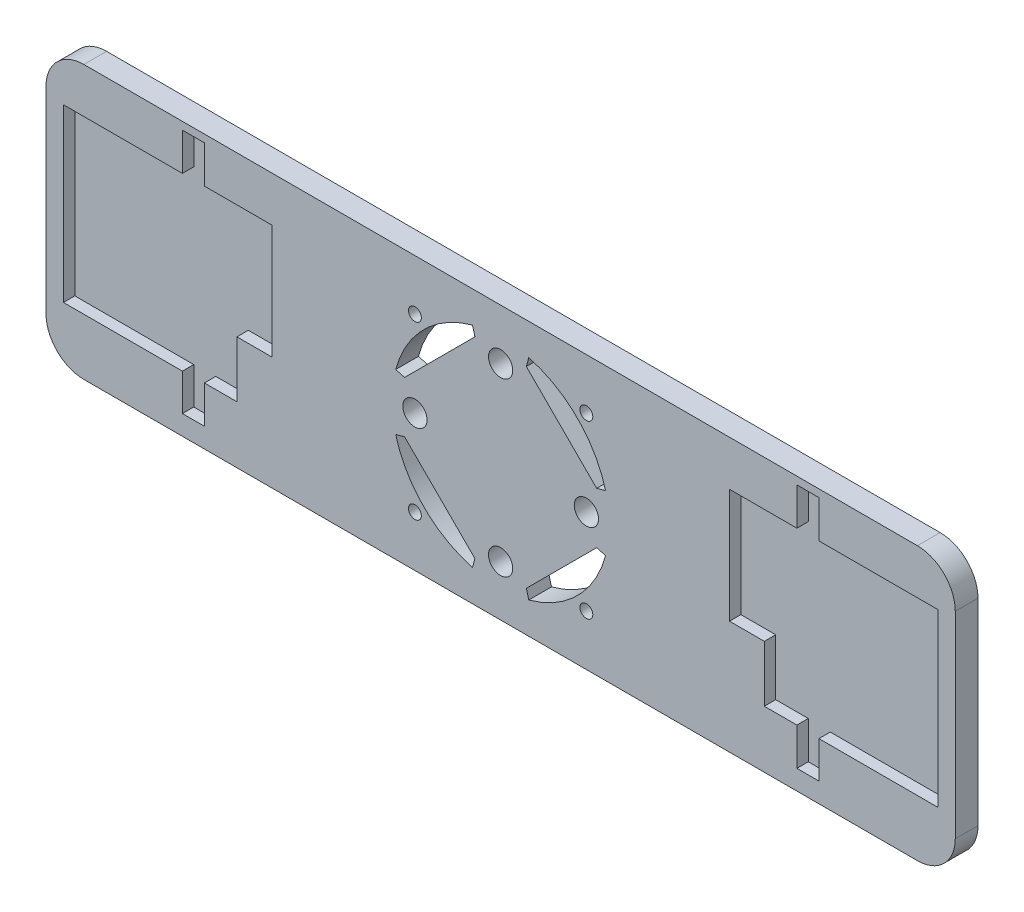
SolidWorks part; units mm, degrees
ref_plane "前视基准面" through (0, 0, 0) normal (0, 0, 1) x (1, 0, 0)
ref_plane "上视基准面" through (0, 0, 0) normal (0, 1, 0) x (1, 0, 0)
ref_plane "右视基准面" through (0, 0, 0) normal (1, 0, 0) x (0, 0, -1)
sketch "草图1" plane through (0, 0, 0) normal (0, 0, 1) x (1, 0, 0)
  line L0 (60, 32.3394) -> (60, 27.7137) construction
  line L1 (0, 0) -> (120, 0)
  line L2 (0, 0) -> (0, 36)
  line L3 (0, 36) -> (120, 36)
  line L4 (120, 0) -> (120, 36)
  line L5 (45.6606, 18) -> (50.2863, 18) construction
  line L6 (54.3431, 23.6569) -> (51.9667, 26.0333) construction
  line L9 (69.2761, 27.2761) -> (87.5831, 45.5831) construction
  line L11 (65.6569, 12.3431) -> (68.0333, 9.9667) construction
  line L12 (50.7239, 8.7239) -> (42.6818, 0.6818) construction
  line L13 (56.6047, 30.6714) -> (56.2887, 31.8508)
  line L14 (63.3953, 30.6714) -> (63.7113, 31.8508)
  line L15 (72.6714, 21.3953) -> (73.8508, 21.7113)
  line L16 (63.3953, 5.3286) -> (63.7113, 4.1492)
  line L17 (72.6714, 14.6047) -> (73.8508, 14.2887)
  line L18 (47.3286, 21.3953) -> (46.1492, 21.7113)
  line L19 (47.3286, 14.6047) -> (46.1492, 14.2887)
  line L20 (56.6047, 5.3286) -> (56.2887, 4.1492)
  line L21 (60, 8.2863) -> (60, 0) construction
  line L22 (69.7137, 18) -> (74.3394, 18) construction
  line L23 (56.6047, 30.6714) -> (47.3286, 21.3953)
  line L24 (47.3286, 14.6047) -> (56.6047, 5.3286)
  line L25 (63.3953, 5.3286) -> (72.6714, 14.6047)
  line L26 (63.3953, 30.6714) -> (72.6714, 21.3953)
  line L27 (50.7239, 27.2761) -> (32.4301, 45.5699) construction
  line L28 (69.2761, 8.7239) -> (76.9756, 1.0244) construction
  circle A8 centre (48.6863, 29.3137) radius 0.85
  circle A9 centre (48.6863, 6.6863) radius 0.85
  circle A10 centre (71.3137, 6.6863) radius 0.85
  circle A11 centre (71.3137, 29.3137) radius 0.85
  circle A16 centre (60, 29.3137) radius 1.6
  circle A17 centre (48.6863, 18) radius 1.6
  circle A18 centre (60, 6.6863) radius 1.6
  circle A19 centre (71.3137, 18) radius 1.6
  arc A23 (46.1492, 14.2887) -> (56.2887, 4.1492) centre (60, 18) ccw
  arc A25 (73.8508, 21.7113) -> (63.7113, 31.8508) centre (60, 18) ccw
  arc A27 (56.2887, 31.8508) -> (46.1492, 21.7113) centre (60, 18) ccw
  arc A28 (63.7113, 4.1492) -> (73.8508, 14.2887) centre (60, 18) ccw
  dimension "D3" = 16
  dimension "D4" = 16
  dimension "D5" = 1.7
  dimension "D6" = 1.7
  dimension "D7" = 8
  dimension "D10" = 15
  dimension "D11" = 15
  dimension "D9" = 3.2
  dimension "D1" = 120
  dimension "D2" = 36
  dimension "D8" = 8
  dimension "D16" = 45
  dimension "D17" = 45
  dimension "D18" = 45
  dimension "D19" = 45
extrude "凸台-拉伸1" add sketch "草图1" along normal blind 3
sketch "草图2" plane through (0, 0, 3) normal (0, 0, 1) x (1, 0, 0)
  line L1 (0, 36) -> (0, 0) construction
  line L2 (120, 0) -> (120, 36) construction
  line L3 (60, 36) -> (60, 0) construction
  line L4 (120, 36) -> (0, 36) construction
  line L5 (0, 0) -> (120, 0) construction
  line L18 (93, 18) -> (120, 18) construction
  line L88 (2.3, 30.05) -> (18, 30.05)
  line L93 (18, 30.05) -> (18, 35)
  line L94 (18, 35) -> (20.9, 35)
  line L95 (20.9, 35) -> (20.9, 30.05)
  line L96 (20.9, 30.05) -> (29.8, 30.05)
  line L98 (29.8, 30.05) -> (29.8, 14.97)
  line L99 (29.8, 14.97) -> (25.2, 14.97)
  line L100 (25.2, 14.97) -> (25.2, 7.55)
  line L101 (25.2, 7.55) -> (20.9, 7.55)
  line L102 (20.9, 7.55) -> (20.9, 2.6)
  line L103 (20.9, 2.6) -> (18, 2.6)
  line L104 (18, 2.6) -> (18, 7.45)
  line L105 (18, 7.45) -> (2.3, 7.45)
  line L107 (2.3, 30.05) -> (2.3, 7.45)
  line L108 (117.7, 30.05) -> (102, 30.05)
  line L109 (102, 30.05) -> (102, 35)
  line L110 (102, 35) -> (99.1, 35)
  line L111 (99.1, 35) -> (99.1, 30.05)
  line L112 (99.1, 30.05) -> (90.2, 30.05)
  line L113 (90.2, 30.05) -> (90.2, 14.97)
  line L114 (90.2, 14.97) -> (94.8, 14.97)
  line L115 (94.8, 14.97) -> (94.8, 7.55)
  line L116 (94.8, 7.55) -> (99.1, 7.55)
  line L117 (99.1, 7.55) -> (99.1, 2.6)
  line L118 (99.1, 2.6) -> (102, 2.6)
  line L119 (102, 2.6) -> (102, 7.45)
  line L120 (102, 7.45) -> (117.7, 7.45)
  line L121 (117.7, 30.05) -> (117.7, 7.45)
  line L122 (20.9, 30.05) -> (20.9, 7.55) construction
  dimension "D1" = 22.6
  dimension "D2" = 15.7
  dimension "D3" = 15.7
  dimension "D4" = 2.9
  dimension "D5" = 4.95
  dimension "D6" = 4.95
  dimension "D7" = 15.08
  dimension "D8" = 4.6
  dimension "D9" = 8.9
  dimension "D10" = 4.3
  dimension "D11" = 29.8
  dimension "D12" = 4.95
  dimension "D13" = 7.42
  dimension "D14" = 90
  dimension "D15" = 1
  dimension "D16" = 1
  dimension "D17" = 2.9
extrude "切除-拉伸1" cut sketch "草图2" against normal blind 1.5
fillet "圆角1" radius 5 4 edges at (120, 36, 1.5) (120, 0, 1.5) (0, 0, 1.5) (0, 36, 1.5)
